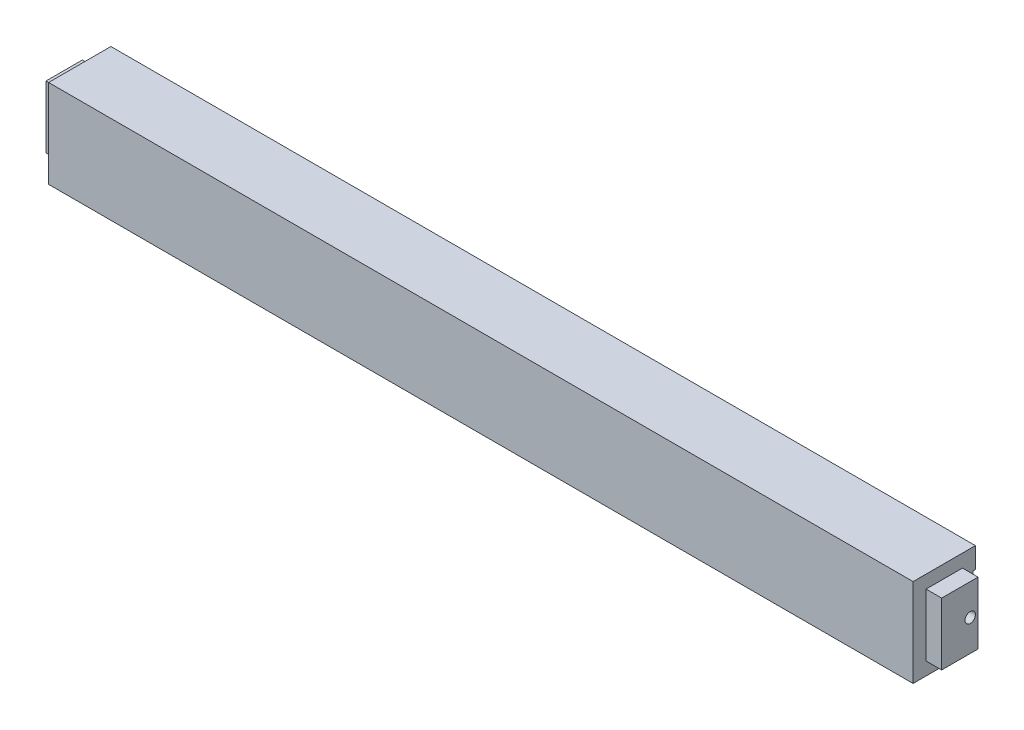
SolidWorks part; units mm, degrees
ref_plane "Front Plane" through (0, 0, 0) normal (0, 0, 1) x (1, 0, 0)
ref_plane "Top Plane" through (0, 0, 0) normal (0, 1, 0) x (1, 0, 0)
ref_plane "Right Plane" through (0, 0, 0) normal (1, 0, 0) x (0, 0, -1)
sketch "Sketch1" plane through (0, 0, 0) normal (0, 0, 1) x (1, 0, 0)
  line L1 (528.6375, 53.975) -> (-528.6375, 53.975)
  line L2 (528.6375, 53.975) -> (528.6375, -53.975)
  line L3 (528.6375, -53.975) -> (-528.6375, -53.975)
  line L4 (-528.6375, 53.975) -> (-528.6375, -53.975)
  line L5 (528.6375, 53.975) -> (-528.6375, -53.975) construction
  line L6 (528.6375, -53.975) -> (-528.6375, 53.975) construction
  point P0 (0, 0)
  dimension "D1" = 1057.275
  dimension "D2" = 107.95
extrude "Boss-Extrude1" add sketch "Sketch1" along normal blind 76.2
sketch "Sketch2" plane through (528.6375, 0, 0) normal (1, 0, 0) x (0, 0, -1)
  line L0 (0, -53.975) -> (0, 53.975) construction
  line L1 (-60.325, 38.1) -> (-15.875, 38.1)
  line L2 (-60.325, 38.1) -> (-60.325, -38.1)
  line L3 (-60.325, -38.1) -> (-15.875, -38.1)
  line L4 (-15.875, 38.1) -> (-15.875, -38.1)
  line L5 (-60.325, 38.1) -> (-15.875, -38.1) construction
  line L6 (-60.325, -38.1) -> (-15.875, 38.1) construction
  line L7 (-76.2, -53.975) -> (0, -53.975) construction
  point P0 (-38.1, 0)
  dimension "D1" = 76.2
  dimension "D2" = 44.45
  dimension "D3" = 15.875
  dimension "D4" = 15.875
extrude "Boss-Extrude2" add sketch "Sketch2" along normal blind 19.05
sketch "Sketch3" plane through (547.6875, 0, 0) normal (1, 0, 0) x (0, 0, -1)
  line L0 (-76.2, -53.975) -> (0, -53.975) construction
  line L1 (0, -53.975) -> (0, 53.975) construction
  circle A0 centre (-25.4, 0) radius 6.35
  dimension "D1" = 12.7
  dimension "D2" = 53.975
  dimension "D3" = 25.4
extrude "Cut-Extrude1" cut sketch "Sketch3" against normal blind 85.725
sketch "Sketch4" plane through (528.6375, 0, 0) normal (1, 0, 0) x (0, 0, -1)
  line L0 (0, -53.975) -> (0, 53.975) construction
  line L1 (0, 28.575) -> (-3.175, 28.575)
  line L2 (0, 28.575) -> (0, 19.05)
  line L3 (0, 19.05) -> (-3.175, 19.05)
  line L4 (-3.175, 28.575) -> (-3.175, 19.05)
  line L5 (-76.2, -53.975) -> (0, -53.975) construction
  dimension "D1" = 3.175
  dimension "D2" = 9.525
  dimension "D3" = 73.025
extrude "Cut-Extrude2" cut sketch "Sketch4" against normal through all
mirror "Mirror1" about plane through (0, 0, 0) normal (1, 0, 0) of "Cut-Extrude1", "Boss-Extrude2"
sketch "Sketch5" plane through (0, 0, 0) normal (0, 0, -1) x (-1, 0, 0)
  line L0 (-528.6375, 0) -> (528.6375, 0) construction
  line L3 (-528.6375, -38.1) -> (-528.6375, 38.1) construction
  line L4 (528.6375, 19.05) -> (528.6375, -53.975) construction
  circle A0 centre (-461.9625, 0) radius 12.7
  circle A1 centre (461.9625, 0) radius 12.7
  dimension "D1" = 25.4
  dimension "D3" = 66.675
  dimension "D2" = 66.675
extrude "Cut-Extrude3" cut sketch "Sketch5" against normal blind 38.1
